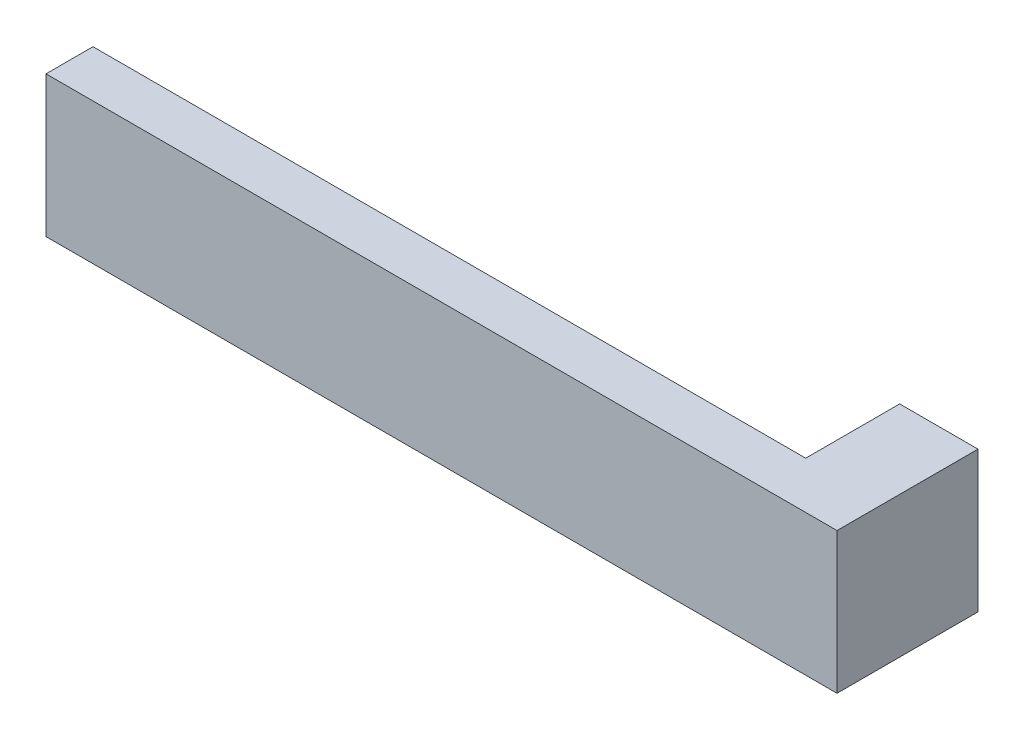
SolidWorks part; units mm, degrees
ref_plane "Front Plane" through (0, 0, 0) normal (0, 0, 1) x (1, 0, 0)
ref_plane "Top Plane" through (0, 0, 0) normal (0, 1, 0) x (1, 0, 0)
ref_plane "Right Plane" through (0, 0, 0) normal (1, 0, 0) x (0, 0, -1)
sketch "Sketch3" plane through (0, 0, 0) normal (0, 1, 0) x (1, 0, 0)
  line L12 (38.5726, -21) -> (38.5726, -12)
  line L13 (38.5726, -12) -> (33.5726, -12)
  line L14 (33.5726, -12) -> (33.5726, -18)
  line L15 (33.5726, -18) -> (-11.9274, -18)
  line L16 (-11.9274, -18) -> (-11.9274, -21)
  line L17 (-11.9274, -21) -> (38.5726, -21)
  dimension "D1" = 3
  dimension "D2" = 50.5
  dimension "D3" = 45.5
  dimension "D4" = 6
extrude "Boss-Extrude1" add sketch "Sketch3" along normal blind 9
